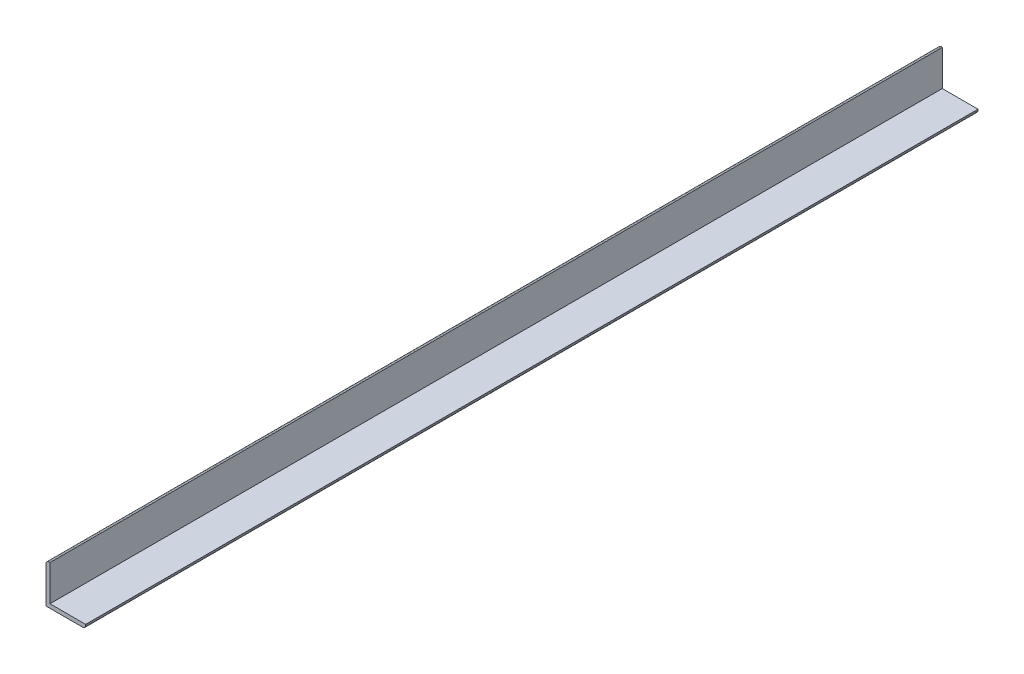
SolidWorks part; units mm, degrees
ref_plane "Спереди" through (0, 0, 0) normal (0, 0, 1) x (1, 0, 0)
ref_plane "Сверху" through (0, 0, 0) normal (0, 1, 0) x (1, 0, 0)
ref_plane "Справа" through (0, 0, 0) normal (1, 0, 0) x (0, 0, -1)
sketch "Эскиз1" plane through (0, 0, 0) normal (0, 0, 1) x (1, 0, 0)
  line L0 (0, 0) -> (37, 0)
  line L1 (40, 3) -> (40, 4)
  line L2 (4, 4) -> (4, 40)
  line L3 (4, 40) -> (3, 40)
  line L4 (0, 37) -> (0, 0)
  line L5 (4, 4) -> (40, 4)
  arc A0 (37, 0) -> (40, 3) centre (37, 3) ccw
  arc A1 (3, 40) -> (0, 37) centre (3, 37) ccw
  point P11 (0, 40)
  dimension "D1" = 4
  dimension "D3" = 3
  dimension "D2" = 36
extrude "Бобышка-Вытянуть1" add sketch "Эскиз1" along a picked direction on the side of the normal blind 900
